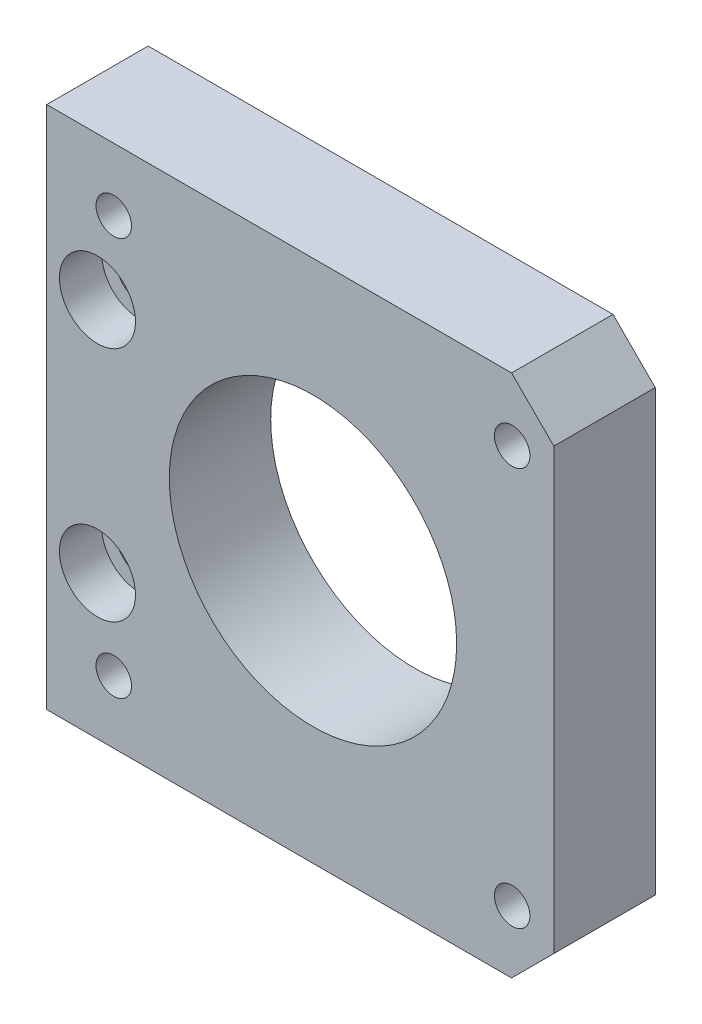
SolidWorks part; units mm, degrees
material "1.0037 (S235JR)"
ref_plane "Płaszczyzna przednia" through (0, 0, 0) normal (0, 0, 1) x (1, 0, 0)
ref_plane "Płaszczyzna górna" through (0, 0, 0) normal (0, 1, 0) x (1, 0, 0)
ref_plane "Płaszczyzna prawa" through (0, 0, 0) normal (1, 0, 0) x (0, 0, -1)
sketch "Szkic1" plane through (0, 0, 0) normal (0, 0, 1) x (1, 0, 0)
  line L0 (12, 331) -> (0, 331) construction
  line L1 (0, 269) -> (60, 269)
  line L2 (0, 269) -> (0, 331)
  line L3 (0, 331) -> (60, 331)
  line L4 (60, 269) -> (60, 331)
  dimension "D1" = 60
extrude "Dodanie-wyciągnięcie1" add sketch "Szkic1" along normal blind 12
sketch "Szkic2" plane through (0, 0, 12) normal (0, 0, 1) x (1, 0, 0)
  circle A0 centre (31.5, 300) radius 17
  circle A1 centre (31.5, 300) radius 16 construction
  dimension "D1" = 34
extrude "Wytnij-wyciągnięcie1" cut sketch "Szkic2" against normal through all
hole_wizard "Pogłębienie walcowe pod M5 Wkręt do części metalowych z łbem sześciokątnym1" positions "Szkic4" profile "Szkic3" counterbore size "M5" standard "Ansi Metric" end condition through all
sketch "Szkic4" plane through (0, 0, 12) normal (0, 0, 1) x (1, 0, 0)
  line L3 (6, 331) -> (6, 269)
  line L4 (6, 331) -> (6, 269)
  line L6 (0, 300) -> (60, 300) construction
  line L7 (0, 331) -> (0, 269) construction
  line L8 (60, 269) -> (60, 331) construction
  point P0 (6, 314)
  point P2 (6, 286)
  dimension "D2" = 28
  dimension "D3" = 14
  dimension "D1" = 6
sketch "Szkic3" plane through (6, 314, 12) normal (1, 0, 0) x (0, -1, 0)
  line L0 (0, 0) -> (0, 12)
  line L1 (0, 12) -> (2.75, 12)
  line L3 (2.75, 12) -> (2.75, 5)
  line L4 (2.75, 5) -> (4.5, 5)
  line L5 (4.5, 5) -> (4.5, 0)
  line L7 (4.5, 0) -> (0, 0)
  line L11 (0, -6.35) -> (0, 107.95) construction
  dimension "Średnica otworu na wylot" = 5.5
  dimension "Głębokość otworu na wylot" = 12
  dimension "Średnica pogłębienia walcowego" = 9
  dimension "Głębokość pogłębienia walcowego" = 5
hole_wizard "Otwór gwintowany M5x0.81" positions "Szkic6" profile "Szkic5" tap size "M5x0.8" standard "Ansi Metric" end condition through all
sketch "Szkic6" plane through (0, 0, 12) normal (0, 0, 1) x (1, 0, 0)
  circle A0 centre (55.07, 323.57) radius 2.5 construction
  circle A1 centre (55.07, 276.43) radius 2.5 construction
  circle A2 centre (7.93, 276.43) radius 2.5 construction
  circle A3 centre (7.93, 323.57) radius 2.5 construction
  point P0 (55.07, 323.57)
  point P2 (55.07, 276.43)
  point P4 (7.93, 323.57)
  point P6 (7.93, 276.43)
sketch "Szkic5" plane through (55.07, 323.57, 12) normal (1, 0, 0) x (0, -1, 0)
  line L0 (0, 0) -> (0, 12)
  line L1 (0, 12) -> (2.1, 12)
  line L2 (2.1, 12) -> (2.1, 0)
  line L5 (2.1, 0) -> (0, 0)
  line L11 (0, -6.35) -> (0, 107.95) construction
  dimension "Średnica zewnętrzna gwintu" = 4.2
  dimension "Głębokość otworu gwintowanego na wylot" = 12
chamfer "Sfazowanie1" distance 5 angle 45 2 edges at (60, 269, 6) (60, 331, 6)
